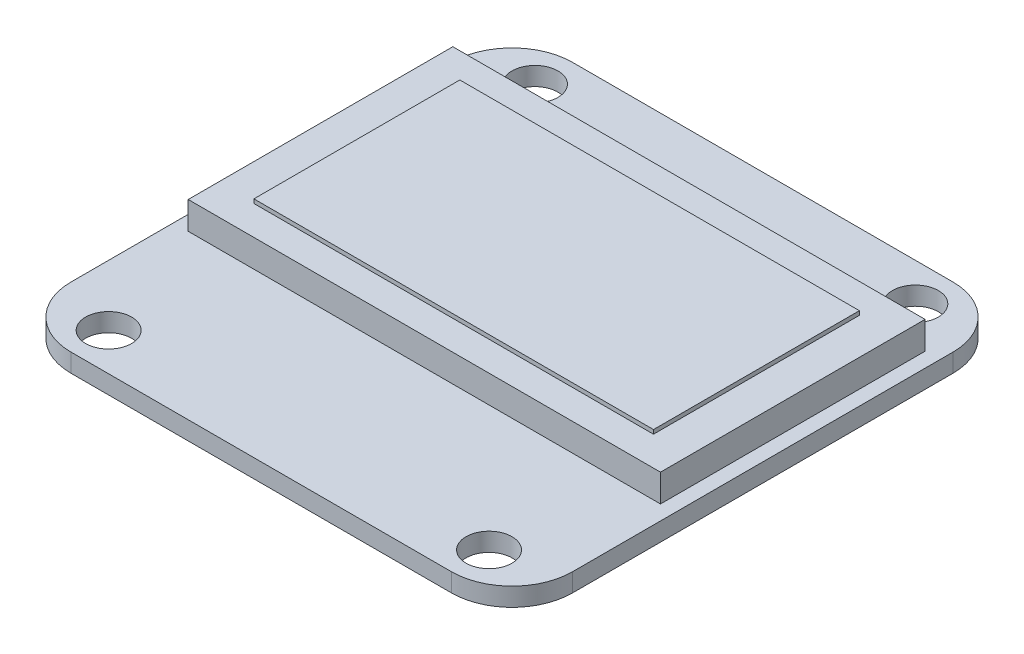
SolidWorks part; units mm, degrees
ref_plane "Front Plane" through (0, 0, 0) normal (0, 0, 1) x (1, 0, 0)
ref_plane "Top Plane" through (0, 0, 0) normal (0, 1, 0) x (1, 0, 0)
ref_plane "Right Plane" through (0, 0, 0) normal (1, 0, 0) x (0, 0, -1)
sketch "Sketch1" plane through (0, 0, 0) normal (0, 1, 0) x (1, 0, 0)
  line L1 (-10.35, -13.65) -> (10.35, -13.65)
  line L2 (-13.65, -10.35) -> (-13.65, 10.35)
  line L3 (-10.35, 13.65) -> (10.35, 13.65)
  line L4 (13.65, -10.35) -> (13.65, 10.35)
  line L5 (-13.65, -13.65) -> (13.65, 13.65) construction
  line L6 (-13.65, 13.65) -> (13.65, -13.65) construction
  line L7 (-10.35, -11.6) -> (10.35, -11.6) construction
  line L8 (-10.35, -11.6) -> (-10.35, 11.6) construction
  line L9 (-10.35, 11.6) -> (10.35, 11.6) construction
  line L10 (10.35, -11.6) -> (10.35, 11.6) construction
  line L11 (-10.35, -11.6) -> (10.35, 11.6) construction
  line L12 (-10.35, 11.6) -> (10.35, -11.6) construction
  arc A0 (-10.35, -13.65) -> (-13.65, -10.35) centre (-10.35, -10.35) cw
  arc A1 (10.35, -13.65) -> (13.65, -10.35) centre (10.35, -10.35) ccw
  arc A2 (10.35, 13.65) -> (13.65, 10.35) centre (10.35, 10.35) cw
  arc A3 (-13.65, 10.35) -> (-10.35, 13.65) centre (-10.35, 10.35) cw
  circle A4 centre (-10.35, 11.6) radius 1.25
  circle A5 centre (10.35, 11.6) radius 1.25
  circle A6 centre (10.35, -11.6) radius 1.25
  circle A7 centre (-10.35, -11.6) radius 1.25
  point P0 (0, 0)
  point P18 (0, 0)
  dimension "D3" = 3.3
  dimension "D6" = 2.5
  dimension "D1" = 27.3
  dimension "D2" = 27.3
  dimension "D4" = 20.7
  dimension "D5" = 23.2
extrude "Boss-Extrude1" add sketch "Sketch1" along normal blind 1
sketch "Sketch2" plane through (0, 1, 0) normal (0, 1, 0) x (1, 0, 0)
  line L0 (10.35, 13.65) -> (-10.35, 13.65) construction
  line L1 (-12.85, 9.63) -> (12.85, 9.63)
  line L2 (-12.85, 9.63) -> (-12.85, -4.77)
  line L3 (-12.85, -4.77) -> (12.85, -4.77)
  line L4 (12.85, 9.63) -> (12.85, -4.77)
  point P4 (0, 9.63)
  dimension "D1" = 25.7
  dimension "D2" = 14.4
  dimension "D3" = 4.02
extrude "Boss-Extrude2" add sketch "Sketch2" along normal blind 1.5
sketch "Sketch4" plane through (0, 2.5, 0) normal (0, 1, 0) x (1, 0, 0)
  line L1 (-10.872, 8.032) -> (10.872, 8.032)
  line L2 (-10.872, 8.032) -> (-10.872, -3.172)
  line L3 (-10.872, -3.172) -> (10.872, -3.172)
  line L4 (10.872, 8.032) -> (10.872, -3.172)
  line L5 (-10.872, 8.032) -> (10.872, -3.172) construction
  line L6 (-10.872, -3.172) -> (10.872, 8.032) construction
  line L8 (-12.85, 2.43) -> (12.85, 2.43) construction
  line L9 (-12.85, 9.63) -> (-12.85, -4.77) construction
  line L10 (12.85, -4.77) -> (12.85, 9.63) construction
  point P0 (0, 2.43)
  point P5 (0, 2.43)
  dimension "D1" = 11.204
  dimension "D2" = 21.744
extrude "Boss-Extrude3" add sketch "Sketch4" along normal blind 0.22
